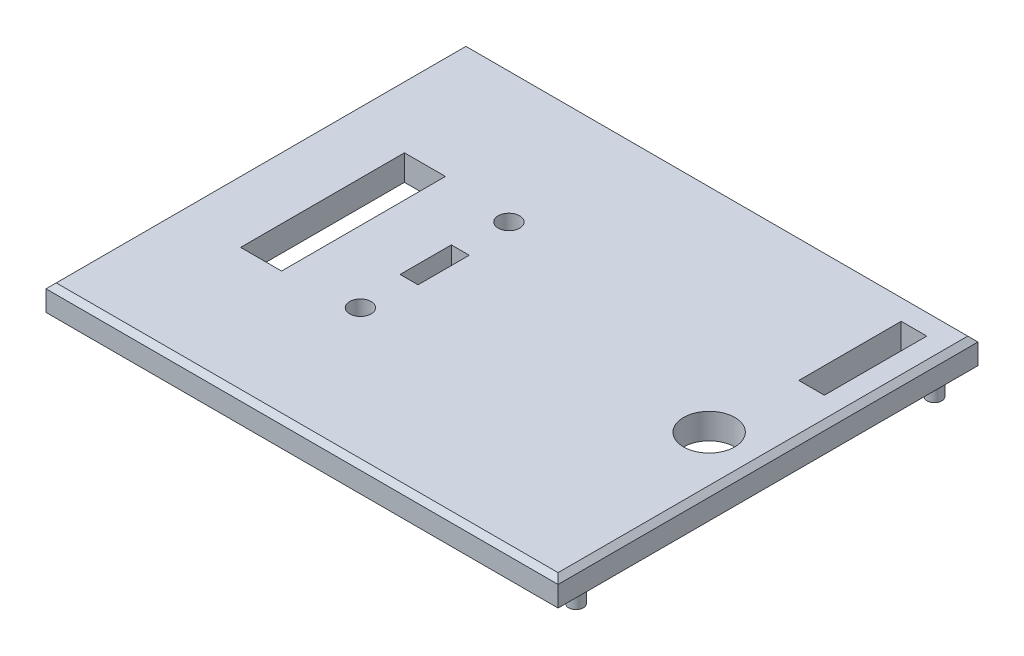
SolidWorks part; units mm, degrees
ref_plane "Front Plane" through (0, 0, 0) normal (0, 0, 1) x (1, 0, 0)
ref_plane "Top Plane" through (0, 0, 0) normal (0, 1, 0) x (1, 0, 0)
ref_plane "Right Plane" through (0, 0, 0) normal (1, 0, 0) x (0, 0, -1)
sketch "Sketch1" plane through (0, 0, 0) normal (0, 1, 0) x (1, 0, 0)
  line L0 (50, 16) -> (50, -41)
  line L1 (-50, -41) -> (50, -41)
  line L2 (-50, -41) -> (-50, 41)
  line L5 (-50, -41) -> (50, 41) construction
  line L6 (-50, 41) -> (50, -41) construction
  line L8 (50, 41) -> (50, 36)
  line L9 (-50, 41) -> (50, 41)
  line L11 (40, 36) -> (40, 16)
  line L12 (45, 16) -> (45, 36)
  line L13 (50, 36) -> (50, 16)
  line L14 (40, 36) -> (45, 36)
  line L15 (45, 16) -> (40, 16)
  line L16 (40, 16) -> (40, -1.5) construction
  line L17 (-55, 0) -> (55, 0) construction
  line L19 (-37, -16) -> (-37, 16)
  line L21 (-13, -16) -> (-13, 16)
  line L22 (-37, -16) -> (-13, 16) construction
  line L23 (-37, 16) -> (-13, -16) construction
  line L24 (-15.1, 14.5) -> (-15.1, -14.5) construction
  line L25 (-29, 16) -> (-29, -16)
  line L26 (-13.35, -5) -> (-16.85, -5)
  line L27 (-13.35, -5) -> (-13.35, 5)
  line L28 (-13.35, 5) -> (-16.85, 5)
  line L29 (-16.85, -5) -> (-16.85, 5)
  line L30 (-13.35, -5) -> (-16.85, 5) construction
  line L31 (-13.35, 5) -> (-16.85, -5) construction
  line L32 (-37, 16) -> (-29, 16)
  line L33 (-37, -16) -> (-29, -16)
  circle A0 centre (40, -1.5) radius 5
  circle A1 centre (-15.1, 14.5) radius 2.1
  circle A2 centre (-15.1, -14.5) radius 2.1
  point P0 (0, 0)
  point P16 (-25, 0)
  point P26 (-15.1, 0)
  point P27 (-15.1, 0)
  dimension "D12" = 10
  dimension "D15" = 4.2
  dimension "D16" = 4.2
  dimension "D1" = 100
  dimension "D2" = 82
  dimension "D3" = 25
  dimension "D4" = 25
  dimension "D5" = 5
  dimension "D6" = 5
  dimension "D7" = 10
  dimension "D8" = 5
  dimension "D9" = 5
  dimension "D10" = 5
  dimension "D11" = 17.5
  dimension "D13" = 32
  dimension "D14" = 24
  dimension "D17" = 29
  dimension "D18" = 2.1
  dimension "D19" = 3.5
  dimension "D20" = 10
  dimension "D21" = 8
  dimension "D22" = 32
  dimension "D23" = 16
extrude "Boss-Extrude1" add sketch "Sketch1" along normal blind 5
chamfer "Chamfer1" distance 1 angle 45 4 edges at (50, 5, 0) (-50, 5, 0) (0, 5, 41) (0, 5, -41)
sketch "Sketch3" plane through (0, 0, 0) normal (0, -1, 0) x (1, 0, 0)
  line L0 (50, 41) -> (47.5, 41) construction
  line L1 (-50, 41) -> (50, 41) construction
  line L2 (47.5, 41) -> (47.5, 35)
  line L3 (0, -55) -> (0, 55) construction
  line L4 (55, 0) -> (-55, 0) construction
  circle A0 centre (47.5, 35) radius 1.435
  circle A1 centre (-47.5, 35) radius 1.435
  circle A2 centre (47.5, -35) radius 1.435
  circle A3 centre (-47.5, -35) radius 1.435
  dimension "D3" = 2.87
  dimension "D1" = 2.5
  dimension "D2" = 6
extrude "Boss-Extrude2" add sketch "Sketch3" along normal blind 3.5
